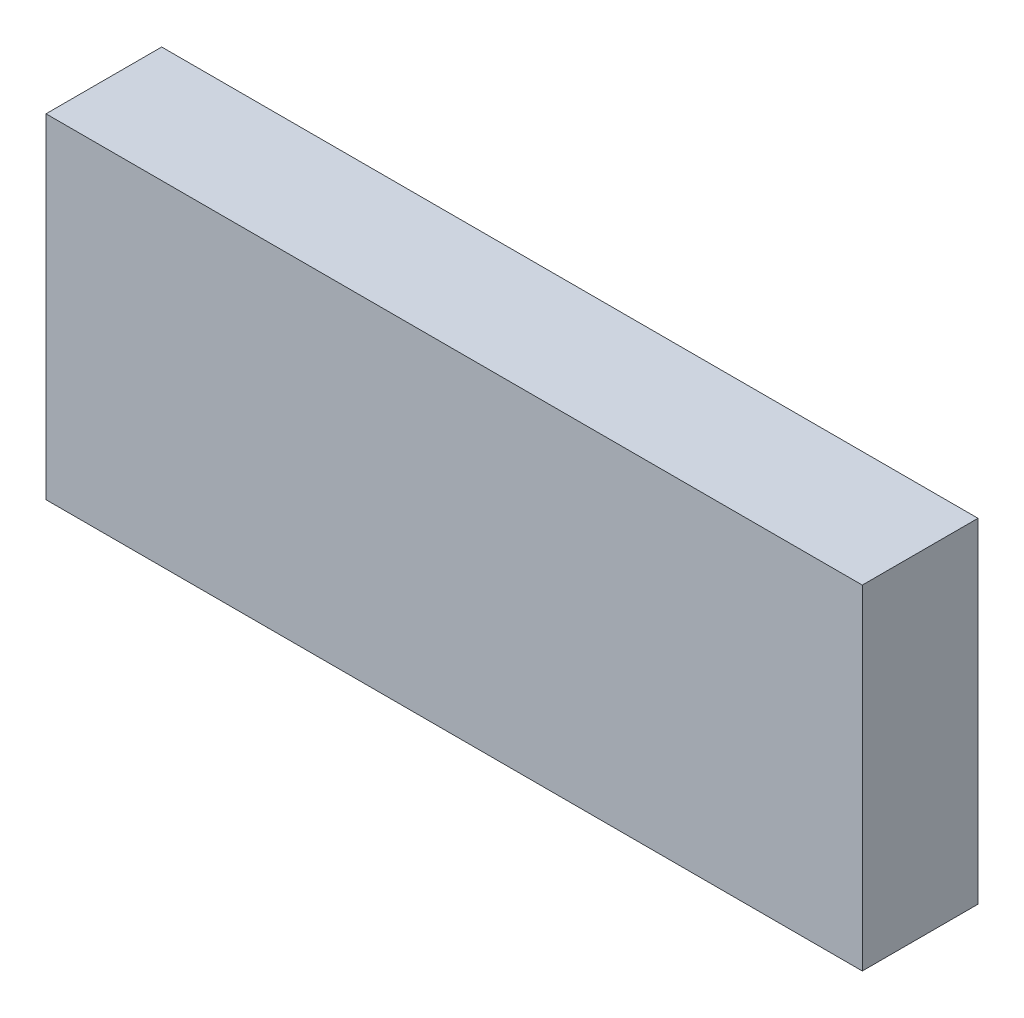
SolidWorks part; units mm, degrees
ref_plane "Front Plane" through (0, 0, 0) normal (0, 0, 1) x (1, 0, 0)
ref_plane "Top Plane" through (0, 0, 0) normal (0, 1, 0) x (1, 0, 0)
ref_plane "Right Plane" through (0, 0, 0) normal (1, 0, 0) x (0, 0, -1)
sketch "Sketch1" plane through (0, 0, 0) normal (0, 0, 1) x (1, 0, 0)
  line L1 (-31.75, -13) -> (31.75, -13)
  line L2 (-31.75, -13) -> (-31.75, 13)
  line L3 (-31.75, 13) -> (31.75, 13)
  line L4 (31.75, -13) -> (31.75, 13)
  line L5 (-31.75, -13) -> (31.75, 13) construction
  line L6 (-31.75, 13) -> (31.75, -13) construction
  point P0 (0, 0)
  dimension "D1" = 26
  dimension "D2" = 63.5
extrude "Boss-Extrude1" add sketch "Sketch1" along normal blind 9
